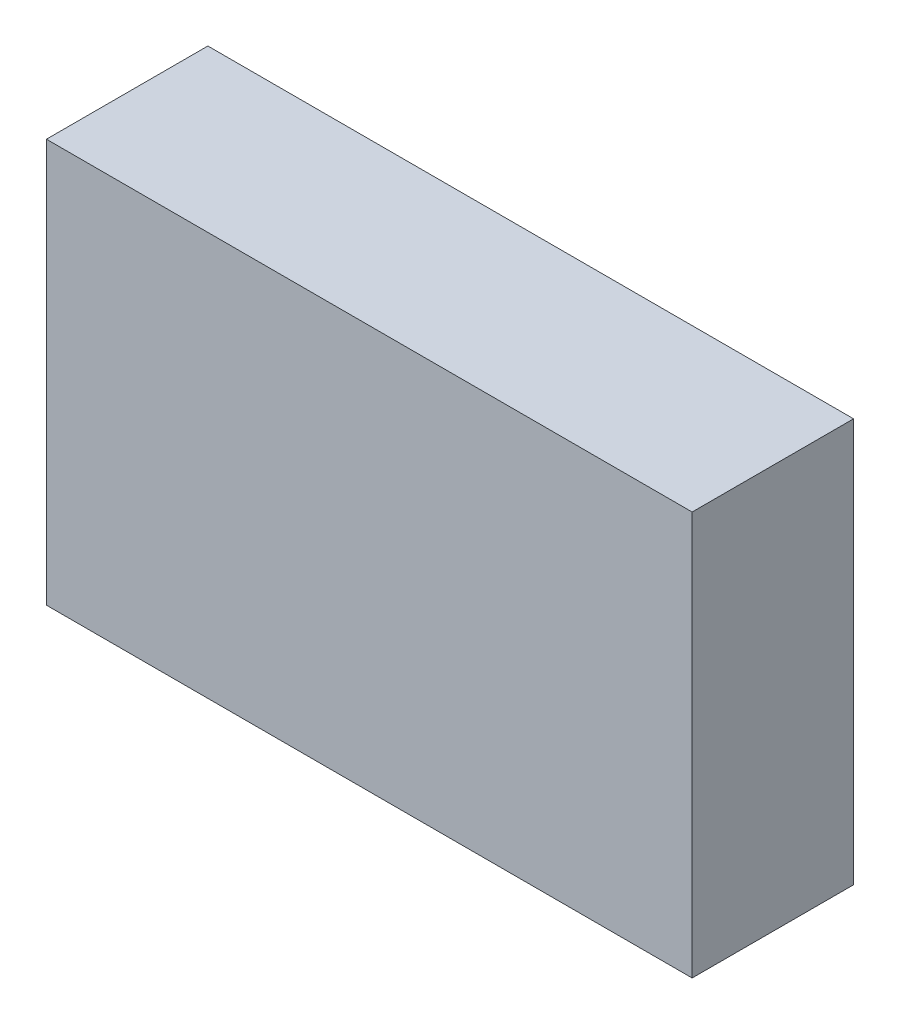
SolidWorks part; units mm, degrees
ref_plane "前视基准面" through (0, 0, 0) normal (0, 0, 1) x (1, 0, 0)
ref_plane "上视基准面" through (0, 0, 0) normal (0, 1, 0) x (1, 0, 0)
ref_plane "右视基准面" through (0, 0, 0) normal (1, 0, 0) x (0, 0, -1)
other "Configuration Table"
sketch "草图1" plane through (0, 0, 0) normal (0, 0, 1) x (1, 0, 0)
  line L1 (-40, -25) -> (40, -25)
  line L2 (-40, -25) -> (-40, 25)
  line L3 (-40, 25) -> (40, 25)
  line L4 (40, -25) -> (40, 25)
  line L5 (-40, -25) -> (40, 25) construction
  line L6 (-40, 25) -> (40, -25) construction
  point P0 (0, 0)
  dimension "D1" = 80
  dimension "D2" = 50
extrude "凸台-拉伸1" add sketch "草图1" along normal blind 20
sketch "草图2" plane through (0, 0, 0) normal (0, 1, 0) x (1, 0, 0)
  line L0 (40, 0) -> (-40, 0) construction
  line L1 (-15, 0) -> (15, 0)
  arc A0 (15, 0) -> (-15, 0) centre (0, 0) ccw
  circle A1 centre (0, 8) radius 2.5
  dimension "D1" = 30
  dimension "D2" = 5
  dimension "D3" = 8
extrude "凸台-拉伸2" add sketch "草图2" along normal mid plane 3
